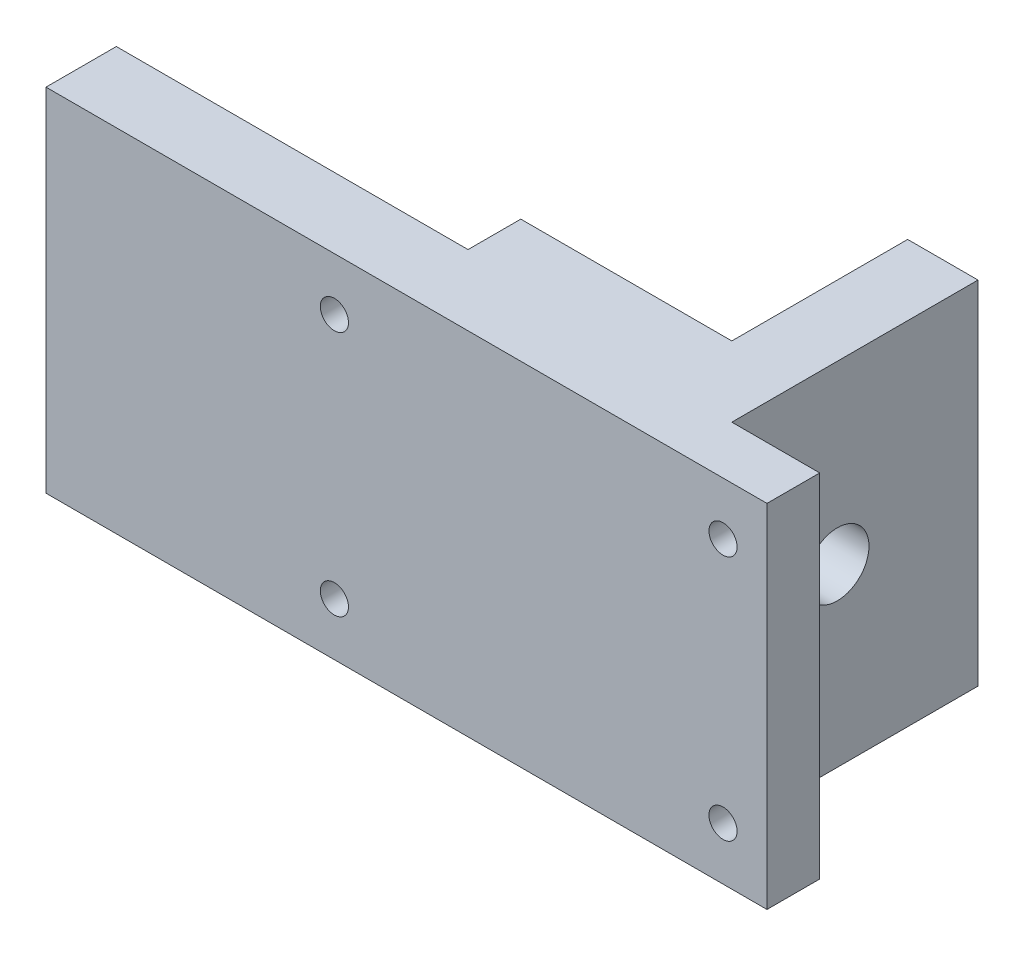
SolidWorks part; units mm, degrees
ref_plane "Front Plane" through (0, 0, 0) normal (0, 0, 1) x (1, 0, 0)
ref_plane "Top Plane" through (0, 0, 0) normal (0, 1, 0) x (1, 0, 0)
ref_plane "Right Plane" through (0, 0, 0) normal (1, 0, 0) x (0, 0, -1)
sketch "Sketch1" plane through (0, 0, 0) normal (0, 1, 0) x (1, 0, 0)
  line L0 (-160, 0) -> (45, 0)
  line L1 (45, 0) -> (45, 15)
  line L2 (45, 15) -> (20, 15)
  line L3 (20, 15) -> (20, 85)
  line L4 (20, 85) -> (0, 85)
  line L5 (0, 85) -> (0, 20)
  line L6 (0, 20) -> (-160, 20)
  line L7 (-160, 20) -> (-160, 0)
  dimension "D1" = 205
  dimension "D2" = 15
  dimension "D3" = 20
  dimension "D4" = 25
  dimension "D5" = 20
  dimension "D6" = 0
  dimension "D7" = 85
extrude "Boss-Extrude2" add sketch "Sketch1" along normal blind 100
sketch "Sketch3" plane through (0, 0, -20) normal (0, 0, -1) x (-1, 0, 0)
  line L1 (60, 71) -> (0, 71)
  line L2 (60, 71) -> (60, 100)
  line L3 (60, 100) -> (0, 100)
  line L4 (0, 71) -> (0, 100)
  line L5 (60, 71) -> (0, 100) construction
  line L6 (60, 100) -> (0, 71) construction
  line L7 (60, 29) -> (0, 29)
  line L8 (60, 29) -> (60, 0)
  line L9 (60, 0) -> (0, 0)
  line L10 (0, 29) -> (0, 0)
  line L11 (60, 29) -> (0, 0) construction
  line L12 (60, 0) -> (0, 29) construction
  point P0 (30, 85.5)
  point P6 (30, 14.5)
  dimension "D1" = 42
  dimension "D2" = 60
  dimension "D3" = 60
  dimension "D4" = 29
extrude "Boss-Extrude3" add sketch "Sketch3" along normal blind 15
sketch "Sketch4" plane through (0, 0, -15) normal (0, 0, -1) x (-1, 0, 0)
  line L0 (-20, 100) -> (-20, 0) construction
  line L1 (-45, 0) -> (-20, 0) construction
  circle A0 centre (-32.5, 85) radius 4
  circle A1 centre (-32.5, 15) radius 4
  dimension "D1" = 8
  dimension "D2" = 8
  dimension "D3" = 12.5
  dimension "D4" = 70
  dimension "D5" = 15
extrude "Cut-Extrude1" cut sketch "Sketch4" against normal blind 15
hole_wizard "Hole2" positions "Sketch7" profile "Sketch8" legacy end condition up to next
sketch "Sketch7" plane through (0, 0, -20) normal (0, 0, -1) x (-1, 0, 0)
  line L0 (160, 100) -> (160, 0) construction
  line L1 (60, 0) -> (160, 0) construction
  point P0 (78, 85)
  point P2 (78, 15)
  dimension "D1" = 82
  dimension "D2" = 82
  dimension "D3" = 70
  dimension "D4" = 15
sketch "Sketch8" plane through (-78, 85, -20) normal (1, 0, 0) x (0, 1, 0)
  line L0 (0, 0) -> (0, 20)
  line L1 (0, 20) -> (4, 20)
  line L2 (4, 20) -> (4, 7.103)
  line L3 (4, 7.103) -> (7.5, 5)
  line L4 (7.5, 5) -> (7.5, 0)
  line L5 (7.5, 0) -> (0, 0)
  line L6 (0, -6.13) -> (0, 109.2824) construction
  line L7 (-4, 7.103) -> (-7.5, 5) construction
  line L8 (0, 20) -> (-4, 20) construction
  dimension "Diameter" = 8
  dimension "Depth" = 20
  dimension "C-Drill Diameter" = 15
  dimension "C-Drill Depth" = 5
  dimension "C-Drill Angle" = 118
sketch "Sketch9" plane through (0, 0, -20) normal (0, 0, -1) x (-1, 0, 0)
  line L0 (60, 0) -> (160, 0) construction
  line L3 (160, 100) -> (160, 0) construction
  circle A0 centre (137.5, 67) radius 3
  circle A1 centre (137.5, 33) radius 3
  dimension "D1" = 6
  dimension "D2" = 6
  dimension "D3" = 34
  dimension "D4" = 33
  dimension "D5" = 22.5
extrude "Cut-Extrude2" cut sketch "Sketch9" against normal blind 15
sketch "Sketch10" plane through (20, 0, 0) normal (1, 0, 0) x (0, 0, -1)
  line L0 (0, 100) -> (0, 0) construction
  line L1 (15, 100) -> (85, 100) construction
  circle A0 centre (45, 50) radius 9
  dimension "D1" = 18
  dimension "D2" = 45
  dimension "D3" = 50
extrude "Cut-Extrude3" cut sketch "Sketch10" against normal blind 52
